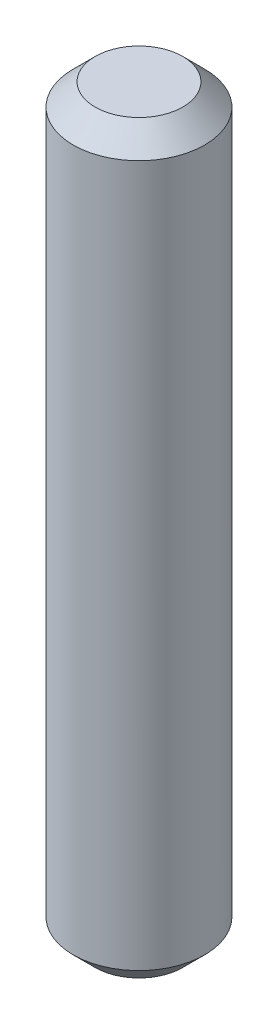
SolidWorks part; units mm, degrees
ref_plane "Front Plane" through (0, 0, 0) normal (0, 0, 1) x (1, 0, 0)
ref_plane "Top Plane" through (0, 0, 0) normal (0, 1, 0) x (1, 0, 0)
ref_plane "Right Plane" through (0, 0, 0) normal (1, 0, 0) x (0, 0, -1)
sketch "Sketch1" plane through (0, 0, 0) normal (0, 0, 1) x (1, 0, 0)
  line L0 (0, 37.2113) -> (0, -36.1963) construction
  line L1 (0, 33.2908) -> (6, 33.2908)
  line L2 (6, 33.2908) -> (6, -34.7092)
  line L3 (6, -34.7092) -> (0, -34.7092)
  line L4 (0, 33.2908) -> (0, -34.7092)
  dimension "D1" = 68
  dimension "D2" = 6
revolve "Revolve1" add sketch "Sketch1" angle 360 about L0
chamfer "Chamfer1" distance 2 angle 45 2 edges at (0, -34.7092, 6) (0, 33.2908, 6)
cosmetic thread "Cosmetic Thread1"
cosmetic thread "Cosmetic Thread2"
